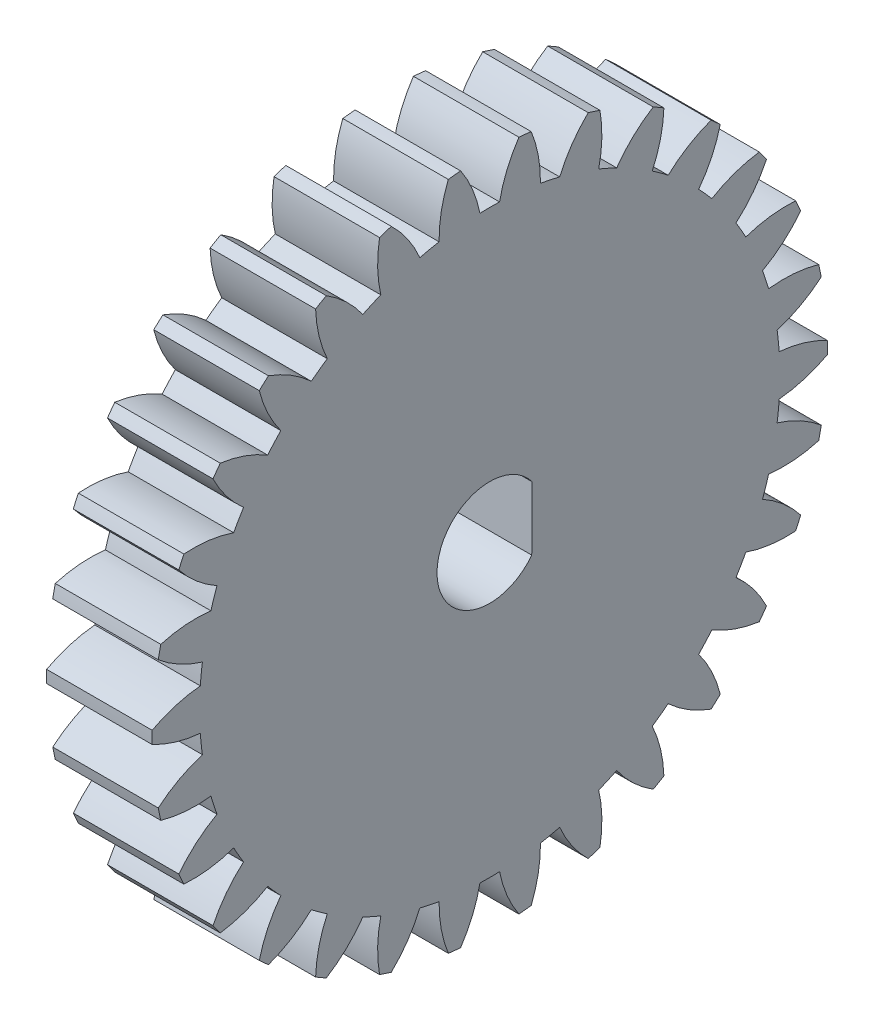
SolidWorks part; units mm, degrees
ref_plane "Plane1" through (0, 0, 0) normal (0, 0, 1) x (1, 0, 0)
ref_plane "Plane2" through (0, 0, 0) normal (0, 1, 0) x (1, 0, 0)
ref_plane "Plane3" through (0, 0, 0) normal (1, 0, 0) x (0, 0, -1)
sketch "HoldingSke" plane through (0, 0, 0) normal (0, 1, 0) x (1, 0, 0)
  line L0 (0, 0) -> (0.866, -0.5)
  line L1 (-15, 0) -> (100, 0) construction
  line L2 (0, 0) -> (-2.1039, 2.3779)
  line L3 (0, 0) -> (-11.863, 4.5341)
  line L4 (0, 0) -> (7.479, 4.318)
  line L5 (0, 0) -> (-46.8476, -17.4728)
  line L6 (0, 0) -> (-4.1448, -2.7965)
  line L7 (-2.1039, 2.3779) -> (8.6586, 51.2059)
  line L8 (-76.2, 54.61) -> (-75.3, 54.61)
  line L9 (-71.009, 38.7566) -> (-53.1078, 45.2721)
  line L10 (-76.2, 71.12) -> (104.1128, 71.12)
  line L11 (0, 0) -> (-5, 0)
  line L12 (-76.2, 101.6) -> (-76.162, 101.6)
  line L13 (24.9733, 27.94) -> (52.9518, 28.4284)
  line L14 (24.9733, 27.94) -> (24.9743, 27.94)
  line L15 (24.9733, 27.94) -> (100.4006, 29.5858)
  line L16 (-63.627, -1) -> (-12.827, -1)
  circle A0 centre (0, 0) radius 2.5
  circle A1 centre (0, 0) radius 13.749
  circle A2 centre (0, 0) radius 37.5
  circle A3 centre (0, 0) radius 2.5
  dimension "MHD" = 27.498
  dimension "Hub_dia" = 75
  dimension "Bore" = 5
  dimension "MBD" = 5
  dimension "Num_teeth" = 30
  dimension "Pitch" = 1
  dimension "Overall_len" = 50
  dimension "Show_teeth" = 30
  dimension "Thickness" = 5
  dimension "OAL" = 50.0001
  dimension "T_dim" = 0.9
  dimension "Ap" = 20
  dimension "H" = 19.05
  dimension "Pitch_radius" = 180.3128
  dimension "Width" = 5
  dimension "Backlash" = 0.038
  dimension "Addendum_fac" = 1
  dimension "Dedendum_fac" = 1.25
  dimension "Clearance_fac" = 0.25
  dimension "Dedendum_add" = 0.001
  dimension "Module" = 1
sketch "BasProSke" plane through (0, 0, 0) normal (0, 1, 0) x (1, 0, 0)
  line L0 (-10, 0) -> (60, 0) construction
  line L1 (0, 0) -> (0, 16)
  line L2 (0, 0) -> (5, 0)
  line L3 (5, 0) -> (5, 16)
  line L4 (5, 16) -> (0, 16)
  dimension "Thickness" = 5
  dimension "Diameter" = 32
revolve "Base-Revolve" add sketch "BasProSke" angle 360 about L0
sketch "TooCutSke" plane through (0, 0, 0) normal (1, 0, 0) x (0, 0, -1)
  line L1 (0, 0) -> (0, 107) construction
  line L2 (0, 0) -> (-0.8515, 14.9758) construction
  line L3 (0, 0) -> (-3.1323, 29.8014) construction
  line L4 (-0.8515, 14.9758) -> (-1.5661, 14.9007) construction
  arc A0 (0.4664, 13.7411) -> (-0.4664, 13.7411) centre (0, 0) ccw
  arc A1 (1.3975, 15.9644) -> (-1.3975, 15.9644) centre (0, 0) ccw
  circle A2 centre (0, 0) radius 15 construction
  circle A3 centre (0, 0) radius 14.0954 construction
  arc A4 (-0.4664, 13.7411) -> (-1.3975, 15.9644) centre (-6.3534, 12.5823) ccw
  arc A5 (1.3975, 15.9644) -> (0.4664, 13.7411) centre (6.3534, 12.5823) ccw
  dimension "Root_dia" = 27.498
  dimension "Overcut_dia" = 32.0508
  dimension "Pitch_dia" = 30
  dimension "Base_dia" = 28.1908
  dimension "Flank_rad" = 6
  dimension "Half_ang" = 6
  dimension "Half_CT" = 0.7185
extrude "ToothCut" cut sketch "TooCutSke" along normal through all
fillet "Breaks" [suppressed] radius 0.02
fillet "RootFillets" [suppressed] radius 0.251
pattern_circular "TeethCuts" count 30 every 12 about axis through (-10, 0, 0) along (1, 0, 0) of "ToothCut", "RootFillets", "Breaks"
sketch "HubNeaOneSke" plane through (0, 0, 0) normal (-1, 0, 0) x (0, 0, 1)
  circle A0 centre (0, 0) radius 13.749
  dimension "Diameter" = 27.498
extrude "HubNearOne" [suppressed] add sketch "HubNeaOneSke" along normal blind 45.0001
sketch "HubNeaBotSke" plane through (0, 0, 0) normal (-1, 0, 0) x (0, 0, 1)
  circle A0 centre (0, 0) radius 13.749
  dimension "Diameter" = 27.498
extrude "HubNearBoth" [suppressed] add sketch "HubNeaBotSke" along normal blind 22.5
ref_plane "FarPln" through (5, 0, 0) normal (1, 0, 0) x (0, 0, -1)
sketch "HubFarSke" plane through (5, 0, 0) normal (1, 0, 0) x (0, 0, -1)
  circle A0 centre (0, 0) radius 13.749
  dimension "Diameter" = 27.498
extrude "HubFar" [suppressed] add sketch "HubFarSke" along normal blind 22.5
sketch "BorSke" plane through (0, 0, 0) normal (1, 0, 0) x (0, 0, -1)
  circle A0 centre (0, 0) radius 2.5
  dimension "Diameter" = 5
extrude "Bore" cut sketch "BorSke" along normal mid plane 100.0001
sketch "KeySke" plane through (0, 0, 0) normal (1, 0, 0) x (0, 0, -1)
  line L0 (-1, 0) -> (-1, 3.4)
  line L1 (-1, 3.4) -> (1, 3.4)
  line L2 (1, 3.4) -> (1, 0)
  line L3 (0, 0) -> (0, 34) construction
  line L4 (-1, 0) -> (1, 0)
  dimension "Offset" = 3.4
  dimension "Width" = 2
extrude "Keyway" [suppressed] cut sketch "KeySke" along normal mid plane 100.0001
pattern_circular "Keyway2" [suppressed] count 2 every 90 about axis through (-10, 0, 0) along (1, 0, 0)
sketch "Esquisse1" plane through (5, 0, 0) normal (1, 0, 0) x (0, 0, -1)
  line L0 (0, 0) -> (2, 0) construction
  line L1 (2, 0) -> (2.0106, 1.4857) construction
  line L2 (0, 0) -> (-2.5, 0) construction
  line L3 (2.0106, 1.4857) -> (2, 0) construction
  line L4 (2, 0) -> (1.9892, -1.5143) construction
  line L5 (1.9892, -1.5143) -> (2.0106, 1.4857)
  circle A0 centre (0, 0) radius 2.5 construction
  arc A1 (2.0106, 1.4857) -> (1.9892, -1.5143) centre (0, 0) ccw
  circle A2 centre (0, 0) radius 3.3569
  dimension "D1" = 4.5
extrude "Boss.-Extru.1" add sketch "Esquisse1" against normal up to surface (5 mm away) up to face at (0, 0, -2.5)
equation "' \"Module@HoldingSke\" = 6.35"
equation "' \"Num_teeth@HoldingSke\" = 12"
equation "' \"Ap@HoldingSke\" =  20"
equation "' \"Ap@HoldingSke\" = 20"
equation "' \"Width@HoldingSke\" = 0.5 * 25.4"
equation "' \"Hub_dia@HoldingSke\"= 1 * 25.4"
equation "' \"Hub_dia@HoldingSke\" = 1 * 25.4"
equation "' \"Overall_len@HoldingSke\" = 1.0 * 25.4"
equation "' \"Bore@HoldingSke\" = 0.75 * 25.4"
equation "' \"T_dim@HoldingSke\" = 0.1 * 25.4"
equation "' \"Width@KeySke\" = 0.25 * 25.4"
equation "' \"Show_teeth@HoldingSke\" = 13"
equation "' \"Backlash@HoldingSke\" = 0.009 * 25.4"
equation "' \"Addendum_fac@HoldingSke\" = 1.0"
equation "' \"Dedendum_fac@HoldingSke\" = 1.25"
equation "' \"Dedendum_add@HoldingSke\" = 0.00005 * 25.4"
equation "' \"Clearance_fac@HoldingSke\" = 0.25"
equation "\"Pitch@HoldingSke\" = 1 / \"Module@HoldingSke\""
equation "\"Overcut_dia@TooCutSke\" = (\"Num_teeth@HoldingSke\" + 2 * \"Addendum_fac@HoldingSke\") / \"Pitch@HoldingSke\" + 0.002 * 25.4"
equation "\"Pitch_dia@TooCutSke\" = \"Num_teeth@HoldingSke\" / \"Pitch@HoldingSke\""
equation "\"Base_dia@TooCutSke\" = \"Num_teeth@HoldingSke\" / \"Pitch@HoldingSke\" * cos((\"Ap@HoldingSke\"  * 3.14159265 / 180))"
equation "\"Root_dia@TooCutSke\" = (\"Num_teeth@HoldingSke\" + 2) / \"Pitch@HoldingSke\" - 2 * (\"Addendum_fac@HoldingSke\" + \"Dedendum_fac@HoldingSke\") / \"Pitch@HoldingSke\" - \"Dedendum_add@HoldingSke\" * 2"
equation "\"Half_ang@TooCutSke\" = 180 / \"Num_teeth@HoldingSke\""
equation "\"Half_CT@TooCutSke\" = \"Num_teeth@HoldingSke\" / \"Pitch@HoldingSke\" * sin((3.14159265 / 2 / \"Num_teeth@HoldingSke\")) / 2 - 7 * \"Backlash@HoldingSke\" / 4"
equation "\"Flank_rad@TooCutSke\" = \"Num_teeth@HoldingSke\" / \"Pitch@HoldingSke\" / 5"
equation "\"Radius@RootFillets\" = \"Clearance_fac@HoldingSke\" / \"Pitch@HoldingSke\" + \"Dedendum_add@HoldingSke\""
equation "\"Break_rad@Breaks\" = 0.02 / \"Pitch@HoldingSke\""
equation "\"Thickness@HoldingSke\" = \"Width@HoldingSke\""
equation "\"OAL@HoldingSke\" = \"Thickness@HoldingSke\""
equation "\"MHD@HoldingSke\" = (\"Num_teeth@HoldingSke\" + 2) / \"Pitch@HoldingSke\" - 2 * (\"Addendum_fac@HoldingSke\" + \"Dedendum_fac@HoldingSke\")  / \"Pitch@HoldingSke\" - \"Dedendum_add@HoldingSke\" * 2"
equation "\"MBD@HoldingSke\" = (\"Num_teeth@HoldingSke\" + 2) / \"Pitch@HoldingSke\" - 2 * (\"Addendum_fac@HoldingSke\" + \"Dedendum_fac@HoldingSke\")  / \"Pitch@HoldingSke\" - \"Dedendum_add@HoldingSke\" * 2 - 0.002 * 25.4"
equation "\"MHD@HoldingSke\" = ((sgn( \"MHD@HoldingSke\" - \"Hub_dia@HoldingSke\" )-1)*( \"MHD@HoldingSke\" - \"Hub_dia@HoldingSke\" ))/-2+ \"Hub_dia@HoldingSke\""
equation "\"MBD@HoldingSke\" = ((sgn( \"MBD@HoldingSke\" - \"Bore@HoldingSke\" )-1)*( \"MBD@HoldingSke\" - \"Bore@HoldingSke\" ))/-2+ \"Bore@HoldingSke\""
equation "\"OAL@HoldingSke\" = ((sgn( \"OAL@HoldingSke\" - \"Overall_len@HoldingSke\" )+1)*( \"OAL@HoldingSke\" - \"Overall_len@HoldingSke\" ))/2 + \"Overall_len@HoldingSke\" + 0.000002 * 25.4"
equation "\"Num_teeth@TeethCuts\" = int( \"Show_teeth@HoldingSke\" ) + 1"
equation "\"Num_teeth@TeethCuts\" = ((sgn( \"Num_teeth@TeethCuts\" - \"Num_teeth@HoldingSke\" )-1)*( \"Num_teeth@TeethCuts\" - \"Num_teeth@HoldingSke\" ))/-2+ \"Num_teeth@HoldingSke\""
equation "\"Num_teeth@TeethCuts\" = ((sgn( \"Num_teeth@TeethCuts\" - 2.0)+1)*( \"Num_teeth@TeethCuts\" - 2.0))/2 +2.0"
equation "\"Angle@TeethCuts\" = 360.0 / \"Num_teeth@HoldingSke\""
equation "\"Diameter@BasProSke\" = (\"Num_teeth@HoldingSke\" + 2 * \"Addendum_fac@HoldingSke\") / \"Pitch@HoldingSke\""
equation "\"Thickness@BasProSke\"  = \"Thickness@HoldingSke\""
equation "' \"Fillet_rad@BasProSke\" =  \"Thickness@HoldingSke\" * 0.05"
equation "' \"Fillet_rad@BasProSke\" = \"Thickness@HoldingSke\" * 0.05"
equation "\"MHD@HoldingSke\" = ((sgn( \"MHD@HoldingSke\" - \"Root_dia@TooCutSke\" )-1)*( \"MHD@HoldingSke\" - \"Root_dia@TooCutSke\" ))/-2+ \"Root_dia@TooCutSke\""
equation "\"Diameter@HubNeaOneSke\" = \"MHD@HoldingSke\""
equation "\"Length@HubNearOne\" = \"OAL@HoldingSke\" - \"Thickness@BasProSke\""
equation "\"Diameter@HubNeaBotSke\" = \"MHD@HoldingSke\""
equation "\"Length@HubNearBoth\" = ( \"OAL@HoldingSke\" - \"Thickness@BasProSke\" ) / 2.0"
equation "\"Thickness@FarPln\" = \"Thickness@BasProSke\""
equation "\"Diameter@HubFarSke\" = \"MHD@HoldingSke\""
equation "\"Length@HubFar\" = ( \"OAL@HoldingSke\" - \"Thickness@BasProSke\" ) / 2.0"
equation "\"Diameter@BorSke\" = \"MBD@HoldingSke\""
equation "\"D1@Bore\" = \"OAL@HoldingSke\" * 2.0"
equation "\"D1@Keyway\" = \"OAL@HoldingSke\" * 2.0"
equation "\"Offset@KeySke\" = \"T_dim@HoldingSke\" + \"MBD@HoldingSke\" / 2.0"
